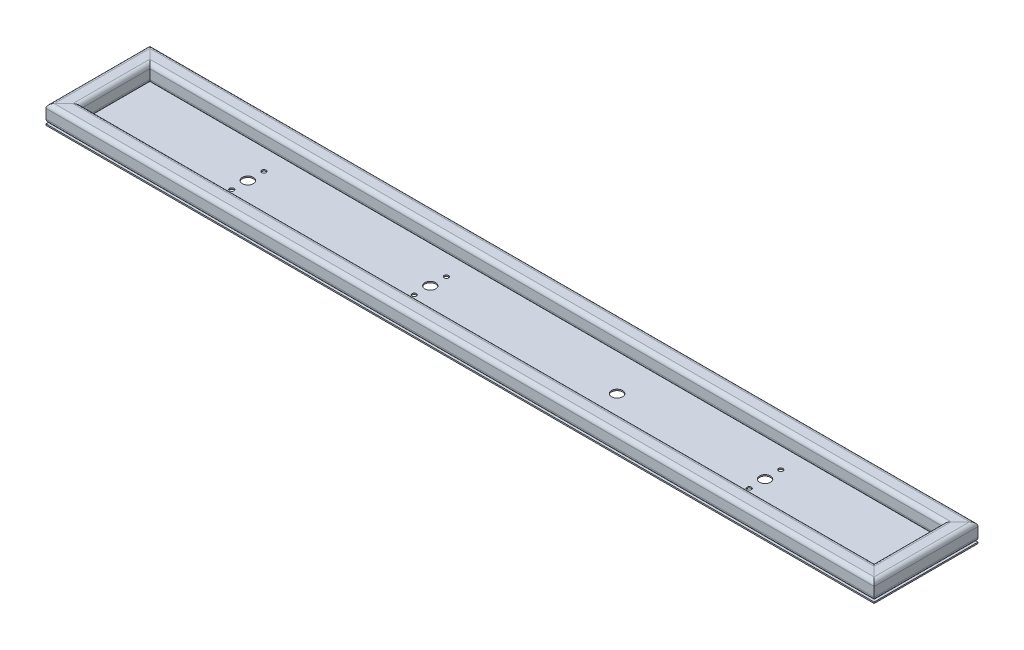
SolidWorks part; units mm, degrees
ref_plane "Alzado" through (0, 0, 0) normal (0, 0, 1) x (1, 0, 0)
ref_plane "Planta" through (0, 0, 0) normal (0, 1, 0) x (1, 0, 0)
ref_plane "Vista lateral" through (0, 0, 0) normal (1, 0, 0) x (0, 0, -1)
sketch "Croquis1" plane through (0, 0, 0) normal (0, 1, 0) x (1, 0, 0)
  line L1 (-598.2, 75) -> (598.2, 75)
  line L2 (-598.2, 75) -> (-598.2, -75)
  line L3 (-598.2, -75) -> (598.2, -75)
  line L4 (598.2, 75) -> (598.2, -75)
  line L5 (-598.2, 75) -> (598.2, -75) construction
  line L6 (-598.2, -75) -> (598.2, 75) construction
  point P0 (0, 0)
  dimension "D1" = 150
  dimension "D2" = 1196.4
other "Tubo cuadrado 2 X 2 X 0.25(1)"
ref_plane "Plano1" through (-585.5, 12.7, -75) normal (0, 0, 1) x (1, 0, 0)
sketch "Sketch1" plane through (-585.5, 12.7, -75) normal (0, 0, 1) x (1, 0, 0)
  line L0 (-6.7, -9.7) -> (6.7, -9.7)
  line L1 (-9.7, -6.7) -> (-9.7, 6.7)
  line L2 (6.7, 9.7) -> (-6.7, 9.7)
  line L3 (9.7, 6.7) -> (9.7, -6.7)
  line L4 (-6.7, -12.7) -> (6.7, -12.7)
  line L5 (-12.7, -6.7) -> (-12.7, 6.7)
  line L6 (6.7, 12.7) -> (-6.7, 12.7)
  line L7 (12.7, 6.7) -> (12.7, -6.7)
  line L8 (0, 0) -> (9.7, 0) construction
  line L9 (0, 0) -> (0, 9.7) construction
  arc A0 (12.7, 6.7) -> (6.7, 12.7) centre (6.7, 6.7) ccw
  arc A1 (6.7, -12.7) -> (12.7, -6.7) centre (6.7, -6.7) ccw
  arc A2 (-12.7, -6.7) -> (-6.7, -12.7) centre (-6.7, -6.7) ccw
  arc A3 (-6.7, 12.7) -> (-12.7, 6.7) centre (-6.7, 6.7) ccw
  arc A4 (-6.7, 9.7) -> (-9.7, 6.7) centre (-6.7, 6.7) ccw
  arc A5 (9.7, 6.7) -> (6.7, 9.7) centre (6.7, 6.7) ccw
  arc A6 (6.7, -9.7) -> (9.7, -6.7) centre (6.7, -6.7) ccw
  arc A7 (-9.7, -6.7) -> (-6.7, -9.7) centre (-6.7, -6.7) ccw
  point P3 (0, 12.7)
  point P4 (12.7, 0)
  point P5 (0, -12.7)
  point P6 (-12.7, 0)
  point P7 (-12.7, 12.7)
  point P8 (-12.7, -12.7)
  point P33 (0, 0)
  point P35 (12.7, -12.7)
  point P36 (12.7, 12.7)
  point P37 (0, 0)
  dimension "D1" = 6
  dimension "Thickness" = 3
  dimension "V_leg" = 25.4
sketch "Croquis3" plane through (0, 0, 0) normal (0, -1, 0) x (1, 0, 0)
  line L1 (598.2, 75) -> (-598.2, 75)
  line L2 (598.2, 75) -> (598.2, -75)
  line L3 (598.2, -75) -> (-598.2, -75)
  line L4 (-598.2, 75) -> (-598.2, -75)
  line L5 (598.2, 75) -> (-598.2, -75) construction
  line L6 (598.2, -75) -> (-598.2, 75) construction
  point P0 (0, 0)
extrude "Saliente-Extruir1" add sketch "Croquis3" along normal blind 1.9 separate body
ref_plane "Plano2" through (0, 0, 0) normal (0, 0, 1) x (1, 0, 0)
sketch "Croquis4" plane through (0, 0, 0) normal (0, 1, 0) x (1, 0, 0)
  line L0 (-382.7228, 25.8523) -> (-381.3281, 23) construction
  line L1 (-381.3281, 23) -> (-378.325, 21.9693) construction
  circle A0 centre (-381.3281, 23) radius 3.175 construction
  circle A1 centre (-381.3281, 23) radius 3.175
  circle A2 centre (-381.5729, 0) radius 7.9375
  circle A3 centre (-381.8178, -23) radius 3.175
  circle A4 centre (-118.0729, 0) radius 7.8396
  circle A5 centre (-117.8281, 23) radius 3.175
  circle A6 centre (-118.3178, -23) radius 3.175
  circle A7 centre (151.7851, 0) radius 7.9375
  circle A8 centre (365.5078, 0) radius 7.9375
  circle A9 centre (365.2629, 23) radius 3.175
  circle A10 centre (365.7527, -23) radius 3.175
  dimension "D1" = 15.875
extrude "Cortar-Extruir1" cut sketch "Croquis4" against normal blind 63.5
